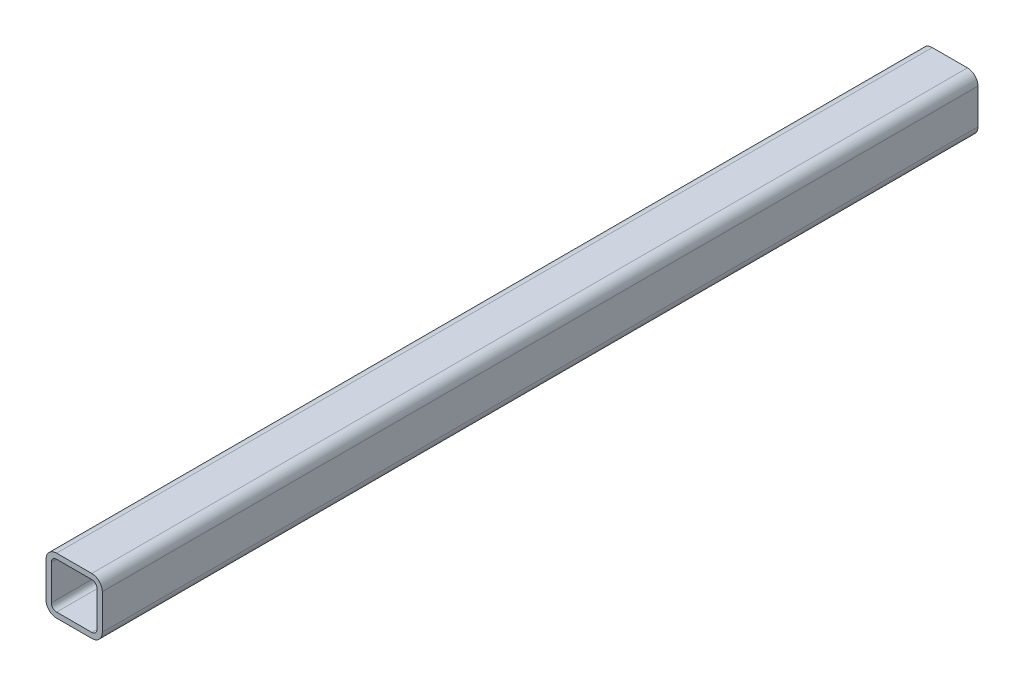
SolidWorks part; units mm, degrees
ref_plane "Płaszczyzna przednia" through (0, 0, 0) normal (0, 0, 1) x (1, 0, 0)
ref_plane "Płaszczyzna górna" through (0, 0, 0) normal (0, 1, 0) x (1, 0, 0)
ref_plane "Płaszczyzna prawa" through (0, 0, 0) normal (1, 0, 0) x (0, 0, -1)
sketch "Szkic1" plane through (0, 0, 0) normal (0, 0, 1) x (1, 0, 0)
  line L1 (9.53, 0) -> (41.27, 0)
  line L2 (0, 9.53) -> (0, 41.27)
  line L3 (9.53, 50.8) -> (41.27, 50.8)
  line L4 (50.8, 9.53) -> (50.8, 41.27)
  line L5 (9.52, 46.04) -> (41.28, 46.04)
  line L6 (4.76, 41.28) -> (4.76, 9.52)
  line L7 (9.52, 4.76) -> (41.28, 4.76)
  line L8 (46.04, 41.28) -> (46.04, 9.52)
  arc A0 (4.76, 9.52) -> (9.52, 4.76) centre (9.52, 9.52) ccw
  arc A1 (41.28, 4.76) -> (46.04, 9.52) centre (41.28, 9.52) ccw
  arc A2 (46.04, 41.28) -> (41.28, 46.04) centre (41.28, 41.28) ccw
  arc A3 (4.76, 41.28) -> (9.52, 46.04) centre (9.52, 41.28) cw
  arc A4 (41.27, 50.8) -> (50.8, 41.27) centre (41.27, 41.27) cw
  arc A5 (50.8, 9.53) -> (41.27, 0) centre (41.27, 9.53) cw
  arc A6 (9.53, 0) -> (0, 9.53) centre (9.53, 9.53) cw
  arc A7 (0, 41.27) -> (9.53, 50.8) centre (9.53, 41.27) cw
  dimension "D7" = 4.76
  dimension "D8" = 9.53
  dimension "D1" = 50.8
  dimension "D2" = 50.8
  dimension "D3" = 41.28
  dimension "D4" = 41.28
  dimension "D5" = 4.76
  dimension "D6" = 4.76
extrude "Dodanie-wyciągnięcie1" add sketch "Szkic1" along normal blind 790.2
